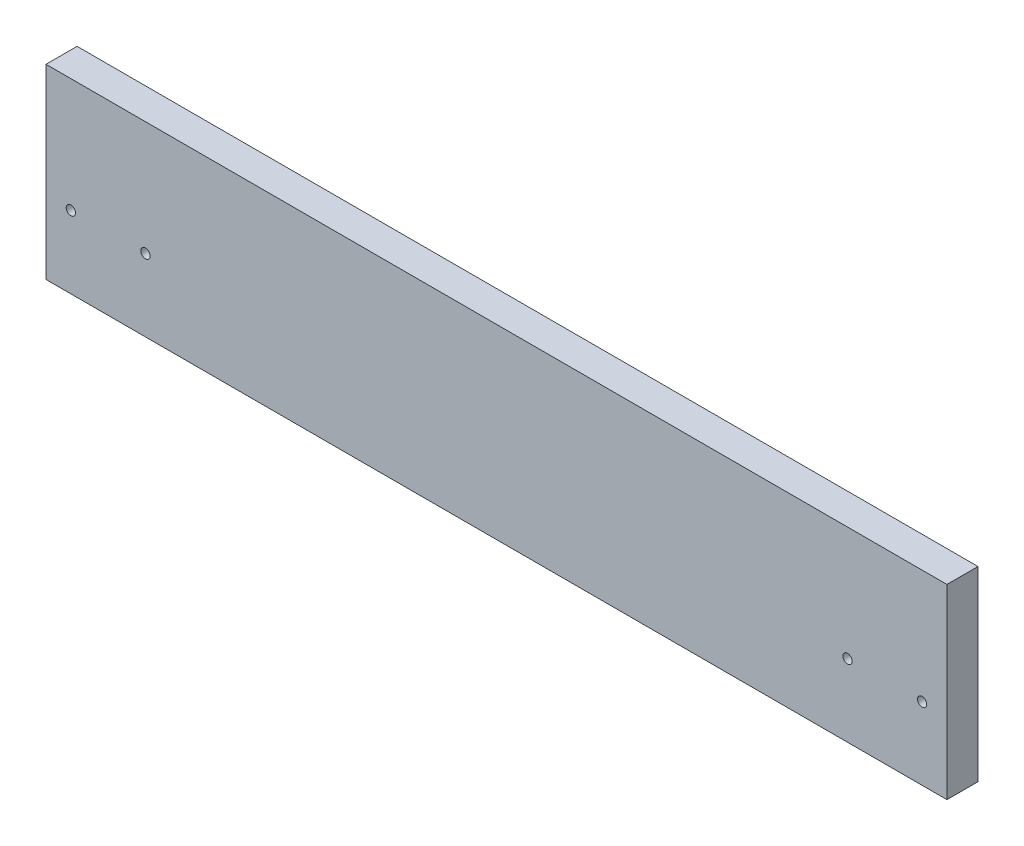
SolidWorks part; units mm, degrees
ref_plane "Спереди" through (0, 0, 0) normal (0, 0, 1) x (1, 0, 0)
ref_plane "Сверху" through (0, 0, 0) normal (0, 1, 0) x (1, 0, 0)
ref_plane "Справа" through (0, 0, 0) normal (1, 0, 0) x (0, 0, -1)
sketch "Эскиз1" plane through (0, 0, 0) normal (0, 0, 1) x (1, 0, 0)
  line L1 (0, 0) -> (290, 0)
  line L2 (0, 0) -> (0, 60)
  line L3 (0, 60) -> (290, 60)
  line L4 (290, 0) -> (290, 60)
  dimension "D1" = 60
  dimension "D2" = 290
extrude "Передняя панель стола" add sketch "Эскиз1" along normal blind 10
sketch "Эскиз3" plane through (0, 0, 10) normal (0, 0, 1) x (1, 0, 0)
  line L0 (145, 60) -> (145, 0) construction
  line L1 (290, 60) -> (0, 60) construction
  line L2 (0, 0) -> (290, 0) construction
  line L3 (0, 23.291) -> (290, 23.291) construction
  line L4 (0, 60) -> (0, 0) construction
  line L5 (290, 0) -> (290, 60) construction
  line L6 (20, 35.0795) -> (20, 6.9182) construction
  circle A0 centre (8, 23.291) radius 1.5
  circle A1 centre (32, 23.291) radius 1.5
  circle A2 centre (282, 23.291) radius 1.5
  circle A3 centre (258, 23.291) radius 1.5
  point P12 (20, 23.291)
  point P13 (8, 23.291)
  dimension "D3" = 3
  dimension "D1" = 125
  dimension "D2" = 12
extrude "Вырез-Вытянуть1" cut sketch "Эскиз3" against normal through all
